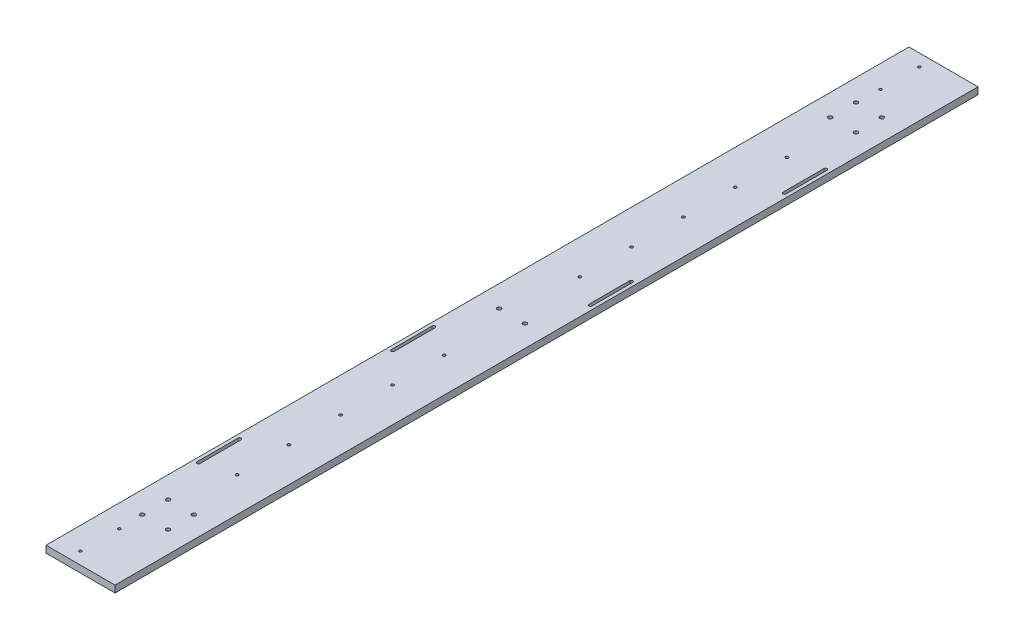
SolidWorks part; units mm, degrees
material "6061 Сплав"
ref_plane "Front" through (0, 0, 0) normal (0, 0, 1) x (1, 0, 0)
ref_plane "Top" through (0, 0, 0) normal (0, 1, 0) x (1, 0, 0)
ref_plane "Right" through (0, 0, 0) normal (1, 0, 0) x (0, 0, -1)
sketch "Эскиз1" plane through (0, 0, 0) normal (0, 0, 1) x (1, 0, 0)
  line L1 (-40, 4) -> (40, 4)
  line L2 (-40, 4) -> (-40, -4)
  line L3 (-40, -4) -> (40, -4)
  line L4 (40, 4) -> (40, -4)
  line L5 (-40, 4) -> (40, -4) construction
  line L6 (-40, -4) -> (40, 4) construction
  point P0 (0, 0)
  dimension "D1" = 80
  dimension "D2" = 8
extrude "Бобышка-Вытянуть1" add sketch "Эскиз1" along normal blind 1000
sketch "Эскиз3" plane through (0, -4, 0) normal (0, -1, 0) x (1, 0, 0)
  line L0 (-40, 1000) -> (-40, 0) construction
  line L1 (-40, 0) -> (40, 0) construction
  circle A0 centre (15, 500) radius 4
  circle A1 centre (-15, 500) radius 4
  dimension "D1" = 30
  dimension "D2" = 25
  dimension "D3" = 500
extrude "Вырез-Вытянуть1" cut sketch "Эскиз3" against normal blind 5
sketch "Эскиз4" plane through (0, 1, 0) normal (0, -1, 0) x (1, 0, 0)
  circle A0 centre (-15, 500) radius 2.25
  circle A1 centre (15, 500) radius 2.25
extrude "Вырез-Вытянуть2" cut sketch "Эскиз4" against normal blind 5
sketch "Эскиз5" plane through (0, -4, 0) normal (0, -1, 0) x (1, 0, 0)
  line L0 (-40, 1000) -> (40, 1000) construction
  line L1 (-40, 1000) -> (-40, 0) construction
  circle A0 centre (-15, 913.6) radius 2.25
  dimension "D1" = 86.4
  dimension "D2" = 25
extrude "Вырез-Вытянуть3" cut sketch "Эскиз5" against normal blind 8
pattern_linear "Линейный массив1" count 2 spacing 30 along (1, 0, 0) count 2 spacing 30 along (0, 0, -1) of "Вырез-Вытянуть3"
sketch "Эскиз6" plane through (0, -4, 0) normal (0, -1, 0) x (1, 0, 0)
  circle A0 centre (-15, 913.6) radius 4
extrude "Вырез-Вытянуть4" cut sketch "Эскиз6" against normal blind 5
pattern_linear "Линейный массив2" count 2 spacing 30 along (1, 0, 0) count 2 spacing 30 along (0, 0, -1) of "Вырез-Вытянуть4"
sketch "Эскиз7" plane through (0, -4, 0) normal (0, -1, 0) x (1, 0, 0)
  line L0 (-40, 1000) -> (-40, 0) construction
  line L1 (-40, 0) -> (40, 0) construction
  circle A0 centre (-15, 86.4) radius 2.25
  dimension "D1" = 25
  dimension "D2" = 86.4
extrude "Вырез-Вытянуть5" cut sketch "Эскиз7" against normal blind 8
pattern_linear "Линейный массив3" count 2 spacing 30 along (1, 0, 0) count 2 spacing 30 along (0, 0, 1) of "Вырез-Вытянуть5"
sketch "Эскиз8" plane through (0, -4, 0) normal (0, -1, 0) x (1, 0, 0)
  circle A0 centre (-15, 86.4) radius 4
extrude "Вырез-Вытянуть6" cut sketch "Эскиз8" against normal blind 5
pattern_linear "Линейный массив4" count 2 spacing 30 along (1, 0, 0) count 2 spacing 30 along (0, 0, 1) of "Вырез-Вытянуть6"
sketch "Эскиз11" plane through (0, -4, 0) normal (0, -1, 0) x (1, 0, 0)
  line L0 (37.5, 220) -> (37.5, 170)
  line L1 (31.5, 170) -> (31.5, 220)
  line L2 (40, 1000) -> (40, 0) construction
  line L3 (-40, 0) -> (40, 0) construction
  line L4 (-31.5, 830) -> (-31.5, 780)
  line L5 (-37.5, 780) -> (-37.5, 830)
  line L6 (-40, 1000) -> (-40, 0) construction
  line L7 (-40, 1000) -> (40, 1000) construction
  arc A0 (31.5, 170) -> (37.5, 170) centre (34.5, 170) ccw
  arc A1 (37.5, 220) -> (31.5, 220) centre (34.5, 220) ccw
  arc A2 (-37.5, 780) -> (-31.5, 780) centre (-34.5, 780) ccw
  arc A3 (-31.5, 830) -> (-37.5, 830) centre (-34.5, 830) ccw
  dimension "D1" = 6
  dimension "D2" = 50
  dimension "D3" = 2.5
  dimension "D4" = 170
  dimension "D5" = 6
  dimension "D6" = 2.5
  dimension "D7" = 170
  dimension "D8" = 50
extrude "Вырез-Вытянуть8" cut sketch "Эскиз11" against normal blind 4
sketch "Эскиз12" plane through (0, 0, 0) normal (0, -1, 0) x (-1, 0, 0)
  line L0 (-36.25, -218.75) -> (-36.25, -171.25)
  line L1 (-32.75, -171.25) -> (-32.75, -218.75)
  line L2 (-37.5, -170) -> (-37.5, -220) construction
  line L3 (32.75, -828.75) -> (32.75, -781.25)
  line L4 (36.25, -781.25) -> (36.25, -828.75)
  line L5 (37.5, -830) -> (37.5, -780) construction
  arc A0 (-32.75, -218.75) -> (-36.25, -218.75) centre (-34.5, -218.75) cw
  arc A1 (-32.75, -171.25) -> (-36.25, -171.25) centre (-34.5, -171.25) ccw
  arc A2 (36.25, -828.75) -> (32.75, -828.75) centre (34.5, -828.75) cw
  arc A3 (36.25, -781.25) -> (32.75, -781.25) centre (34.5, -781.25) ccw
  arc A5 (37.5, -780) -> (31.5, -780) centre (34.5, -780) ccw construction
  point P20 (34.5, -777)
  point P21 (0, 0)
  dimension "D1" = 3.5
  dimension "D2" = 1.25
  dimension "D3" = 47.5
  dimension "D4" = 1.25
  dimension "D5" = 3.5
  dimension "D6" = 1.25
  dimension "D7" = 47.5
  dimension "D8" = 4.25
extrude "Вырез-Вытянуть9" cut sketch "Эскиз12" against normal blind 5
pattern_linear "Линейный массив6" count 2 spacing 225 along (0, 0, 1) count 2 spacing 225 along (0, 0, -1) of "Вырез-Вытянуть8", "Вырез-Вытянуть9"
sketch "Эскиз13" plane through (0, -4, 0) normal (0, -1, 0) x (1, 0, 0)
  line L1 (-40, 0) -> (40, 0) construction
  circle A0 centre (-14, 59) radius 1.5
  circle A1 centre (-14, 14) radius 1.5
  dimension "D1" = 14
  dimension "D2" = 45
extrude "Вырез-Вытянуть10" cut sketch "Эскиз13" against normal blind 8
sketch "Эскиз14" plane through (0, -4, 0) normal (0, -1, 0) x (1, 0, 0)
  circle A0 centre (-14, 59) radius 3
  circle A1 centre (-14, 14) radius 3
extrude "Вырез-Вытянуть11" cut sketch "Эскиз14" against normal blind 4
pattern_linear "Линейный массив8" count 2 spacing 927 along (0, 0, 1) of "Вырез-Вытянуть11", "Вырез-Вытянуть10"
sketch "Эскиз15" plane through (0, -4, 0) normal (0, -1, 0) x (1, 0, 0)
  line L0 (40, 1000) -> (40, 0) construction
  line L1 (40, 1000) -> (-40, 1000) construction
  circle A0 centre (0, 421.45) radius 1.65
  point P4 (0, 1000)
  dimension "D1" = 40
  dimension "D2" = 578.55
extrude "Вырез-Вытянуть12" cut sketch "Эскиз15" against normal blind 10
pattern_linear "Линейный массив9" count 5 spacing 60 along (0, 0, -1) of "Вырез-Вытянуть12"
sketch "Эскиз16" plane through (0, -4, 0) normal (0, -1, 0) x (1, 0, 0)
  line L0 (40, 1000) -> (40, 0) construction
  circle A0 centre (0, 578.55) radius 1.65
  dimension "D1" = 40
  dimension "D2" = 578.55
extrude "Вырез-Вытянуть13" cut sketch "Эскиз16" against normal blind 10
pattern_linear "Линейный массив10" count 5 spacing 60 along (0, 0, 1) of "Вырез-Вытянуть13"
